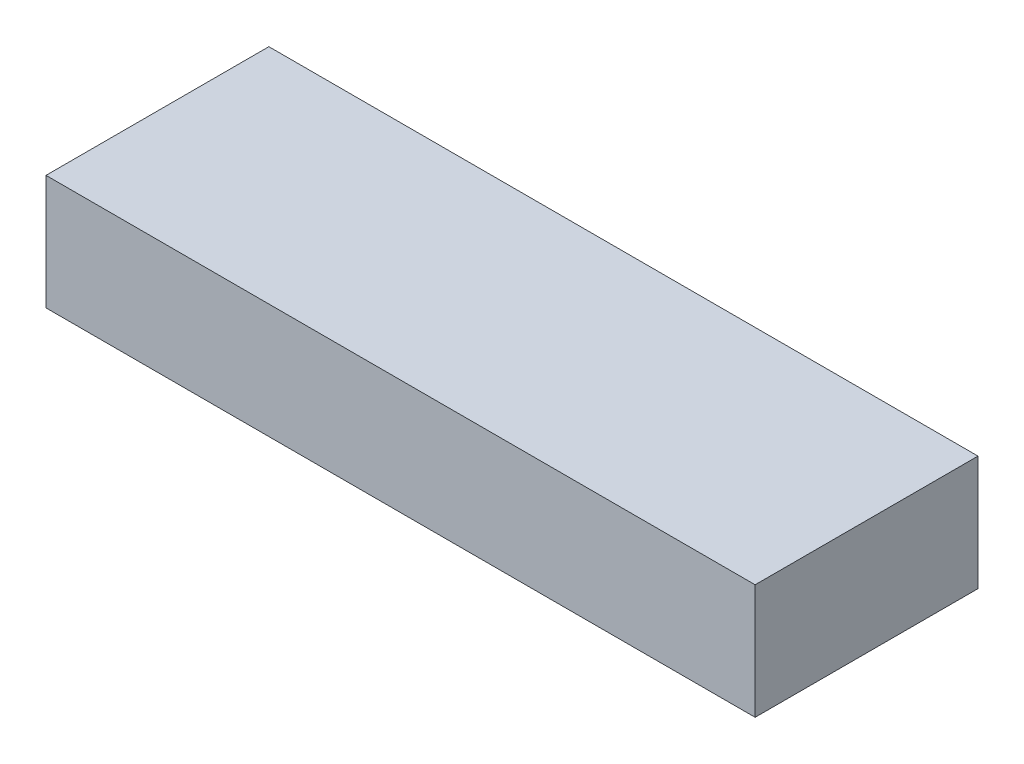
SolidWorks part; units mm, degrees
ref_plane "Front Plane" through (0, 0, 0) normal (0, 0, 1) x (1, 0, 0)
ref_plane "Top Plane" through (0, 0, 0) normal (0, 1, 0) x (1, 0, 0)
ref_plane "Right Plane" through (0, 0, 0) normal (1, 0, 0) x (0, 0, -1)
sketch "Sketch1" plane through (0, 0, 0) normal (0, 1, 0) x (1, 0, 0)
  line L1 (-52.5, -16.5) -> (52.5, -16.5)
  line L2 (-52.5, -16.5) -> (-52.5, 16.5)
  line L3 (-52.5, 16.5) -> (52.5, 16.5)
  line L4 (52.5, -16.5) -> (52.5, 16.5)
  line L5 (-52.5, -16.5) -> (52.5, 16.5) construction
  line L6 (-52.5, 16.5) -> (52.5, -16.5) construction
  point P0 (0, 0)
  dimension "D1" = 33
  dimension "D2" = 105
extrude "Boss-Extrude1" add sketch "Sketch1" along normal blind 17
